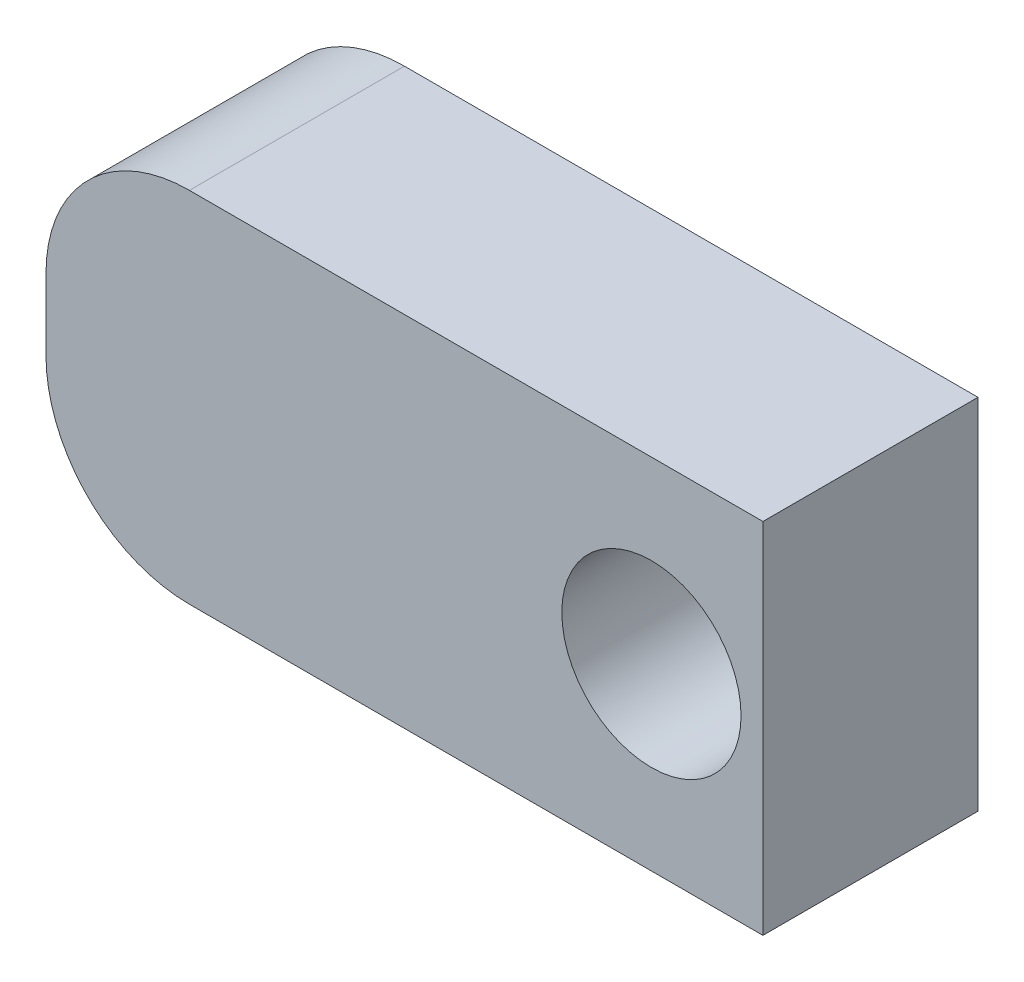
SolidWorks part; units mm, degrees
ref_plane "Front Plane" through (0, 0, 0) normal (0, 0, 1) x (1, 0, 0)
ref_plane "Top Plane" through (0, 0, 0) normal (0, 1, 0) x (1, 0, 0)
ref_plane "Right Plane" through (0, 0, 0) normal (1, 0, 0) x (0, 0, -1)
sketch "Sketch1" plane through (0, 0, 0) normal (0, 0, 1) x (1, 0, 0)
  line L0 (-29.3111, 0) -> (25.7244, 0) construction
  line L1 (-6, 5) -> (10, 5)
  line L2 (-10, 1) -> (-10, -1)
  line L3 (-6, -5) -> (10, -5)
  line L4 (10, 5) -> (10, -5)
  line L5 (-10, 5) -> (10, -5) construction
  line L6 (-10, -5) -> (10, 5) construction
  arc A0 (-10, -1) -> (-6, -5) centre (-6, -1) ccw
  arc A1 (-6, 5) -> (-10, 1) centre (-6, 1) ccw
  circle A2 centre (6.8897, 0) radius 2.5
  point P0 (0, 0)
  dimension "D3" = 4
  dimension "D1" = 20
  dimension "D2" = 10
extrude "Boss-Extrude1" add sketch "Sketch1" along normal blind 6
